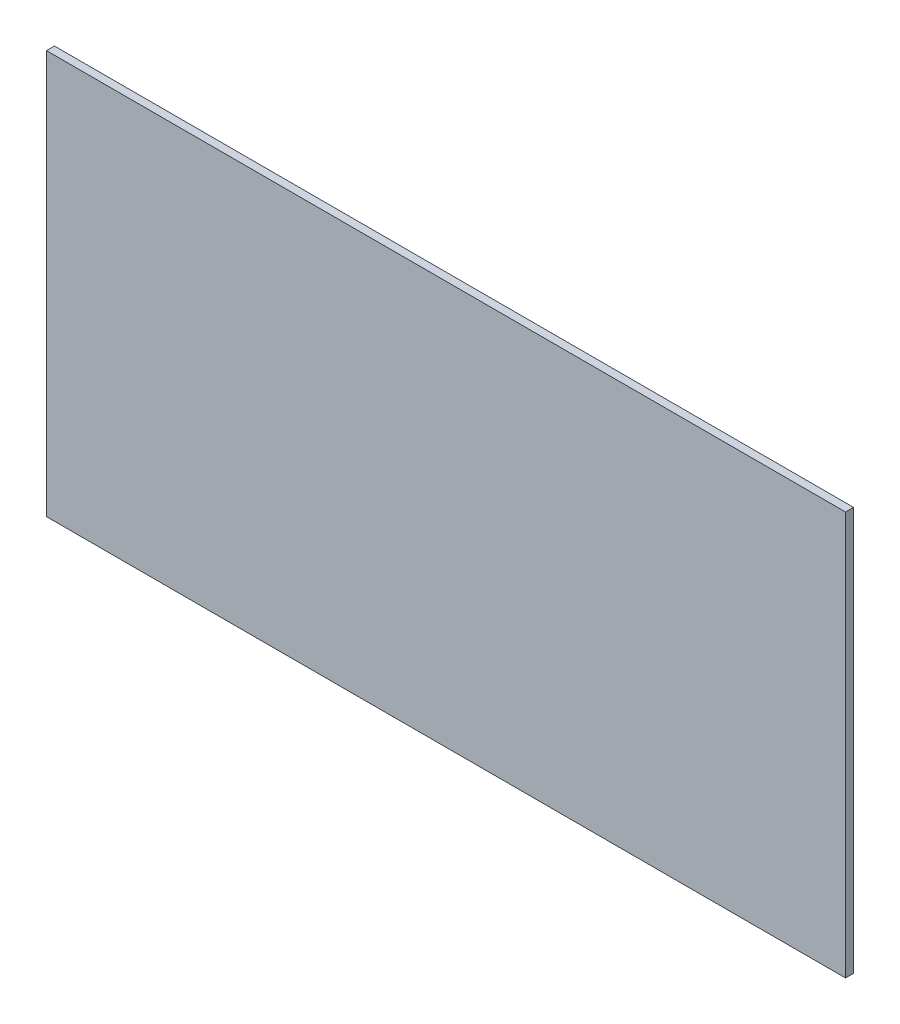
SolidWorks part; units mm, degrees
ref_plane "Front Plane" through (0, 0, 0) normal (0, 0, 1) x (1, 0, 0)
ref_plane "Top Plane" through (0, 0, 0) normal (0, 1, 0) x (1, 0, 0)
ref_plane "Right Plane" through (0, 0, 0) normal (1, 0, 0) x (0, 0, -1)
sketch "Sketch1" plane through (0, 0, 0) normal (0, 0, 1) x (1, 0, 0)
  line L1 (-127, 64.135) -> (127, 64.135)
  line L2 (-127, 64.135) -> (-127, -64.135)
  line L3 (-127, -64.135) -> (127, -64.135)
  line L4 (127, 64.135) -> (127, -64.135)
  line L5 (-127, 64.135) -> (127, -64.135) construction
  line L6 (-127, -64.135) -> (127, 64.135) construction
  point P0 (0, 0)
  dimension "D1" = 254
  dimension "D2" = 128.27
extrude "Boss-Extrude1" add sketch "Sketch1" along normal mid plane 2.54
